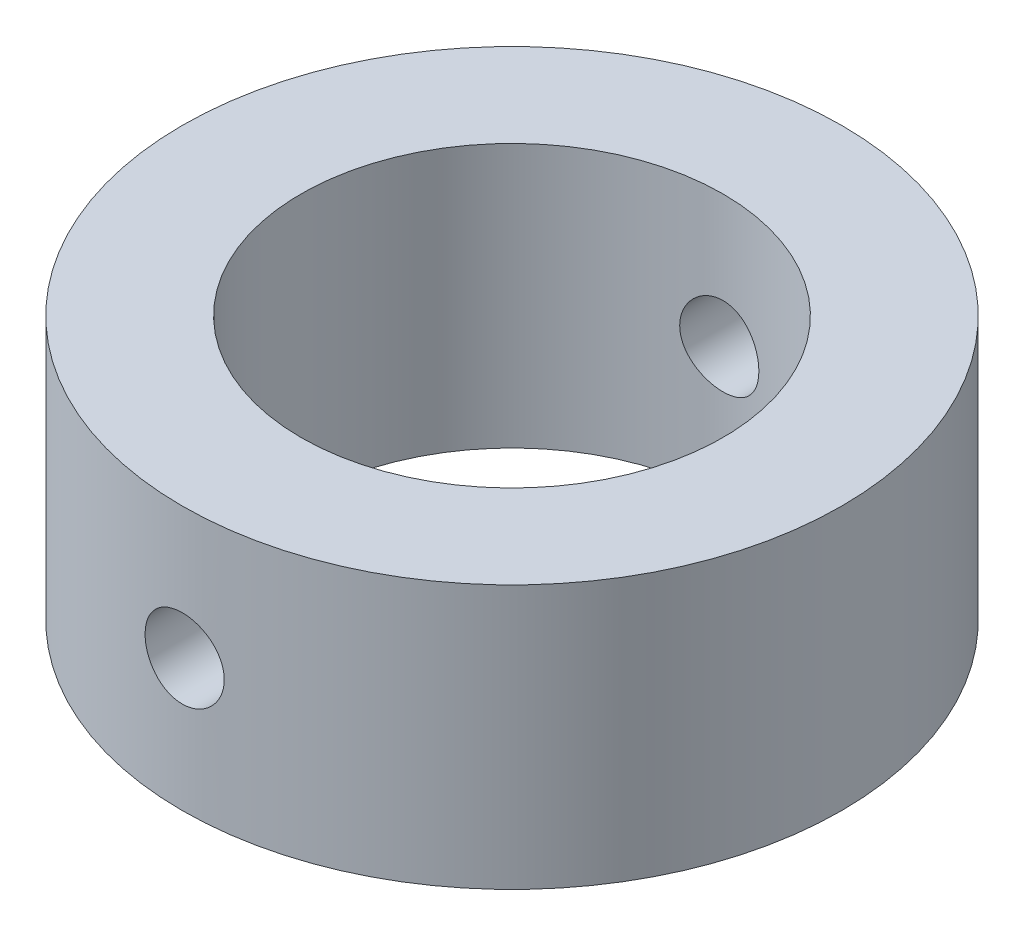
SolidWorks part; units mm, degrees
material "Copper"
ref_plane "Front Plane" through (0, 0, 0) normal (0, 0, 1) x (1, 0, 0)
ref_plane "Top Plane" through (0, 0, 0) normal (0, 1, 0) x (1, 0, 0)
ref_plane "Right Plane" through (0, 0, 0) normal (1, 0, 0) x (0, 0, -1)
sketch "Sketch1" plane through (0, 0, 0) normal (0, 1, 0) x (1, 0, 0)
  circle A0 centre (0, 0) radius 12.5
  circle A1 centre (0, 0) radius 8
  dimension "D1" = 25
  dimension "D2" = 16
extrude "Boss-Extrude1" add sketch "Sketch1" along normal blind 10
sketch "Sketch2" plane through (0, 0, 0) normal (0, 0, 1) x (1, 0, 0)
  circle A0 centre (0, 5) radius 1.5
  point P2 (0, 0)
  dimension "D2" = 3
  dimension "D1" = 5
extrude "Cut-Extrude1" cut sketch "Sketch2" against normal mid plane 40
